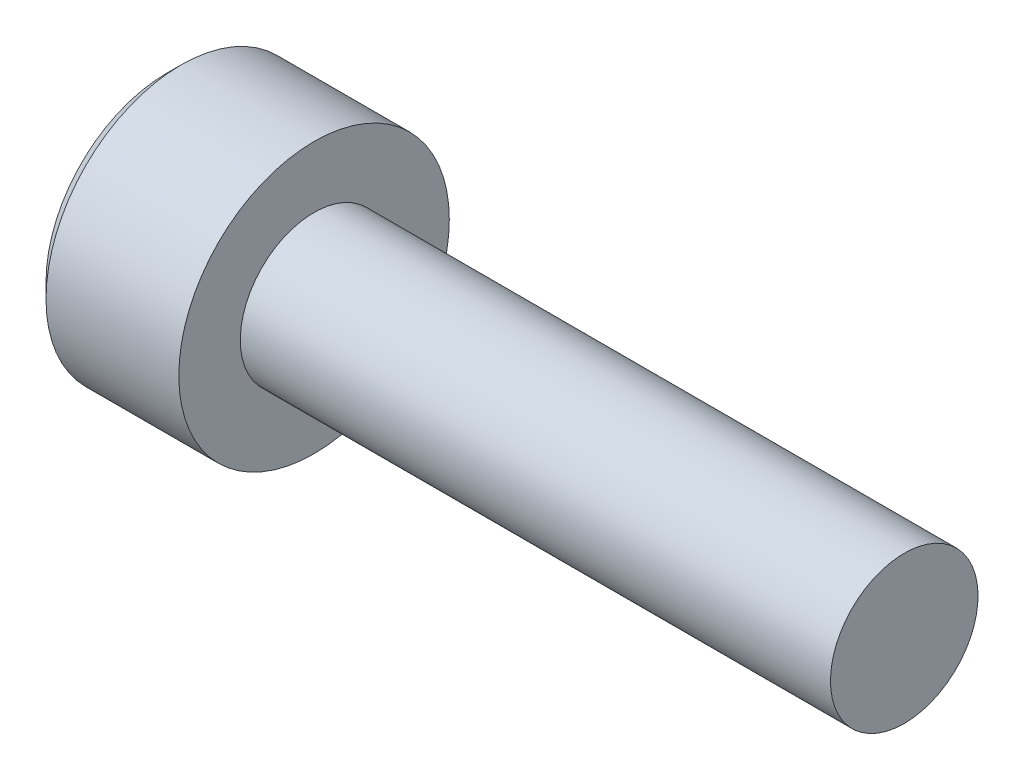
SolidWorks part; units mm, degrees
material "SUS304相当"
ref_plane "Front Plane" through (0, 0, 0) normal (0, 0, 1) x (1, 0, 0)
ref_plane "Top Plane" through (0, 0, 0) normal (0, 1, 0) x (1, 0, 0)
ref_plane "Right Plane" through (0, 0, 0) normal (1, 0, 0) x (0, 0, -1)
sketch "Sketch1" plane through (0, 0, 0) normal (0, 0, 1) x (1, 0, 0)
  line L0 (-3, 0) -> (12, 0) construction
  line L1 (0, 1.5) -> (12, 1.5)
  line L3 (-3, 0) -> (12, 0)
  line L4 (12, 1.5) -> (12, 0)
  line L6 (0, 1.5) -> (0, 2.75)
  line L7 (0, 2.75) -> (-3, 2.75)
  line L8 (-3, 0) -> (-3, 2.75)
  dimension "L" = 12
  dimension "M" = 3
  dimension "E" = 3
  dimension "A" = 5.5
revolve "Revolve1" add sketch "Sketch1" about L0
cosmetic thread "Thread1" parameters "L_s"=12, "ATD"=2.459
sketch "Sketch2" plane through (0, 0, 0) normal (0, 0, 1) x (1, 0, 0)
  line L0 (-3, 0) -> (-0.9489, 0) construction
  line L1 (-3, 0) -> (12, 0) construction
  line L2 (-0.9489, 0) -> (-1.7, 1.25)
  line L3 (-1.7, 1.25) -> (-3, 1.25)
  line L4 (-3, 0) -> (-3, 2.75) construction
  line L5 (-3, 1.25) -> (-3, 0)
  line L6 (-3, 0) -> (-0.9489, 0)
  dimension "MSM_1" = 1.3
  dimension "FIX_2" = 59
revolve "Cut-Revolve1" cut sketch "Sketch2" about L0
sketch "Sketch3" plane through (-3, 0, 0) normal (-1, 0, 0) x (0, 0, 1)
  line L0 (0, -3.025) -> (0, 3.025) construction
  line L1 (1.25, 0.7217) -> (0, 1.4434)
  line L2 (0, 1.4434) -> (-1.25, 0.7217)
  line L3 (-1.25, 0.7217) -> (-1.25, -0.7217)
  line L4 (-1.25, -0.7217) -> (0, -1.4434)
  line L5 (0, -1.4434) -> (1.25, -0.7217)
  line L6 (1.25, -0.7217) -> (1.25, 0.7217)
  circle A0 centre (0, 0) radius 1.25 construction
extrude "Cut-Extrude1" cut sketch "Sketch3" against normal blind 1.3
chamfer "Chamfer1" distance 0.3 1 edges at (-3, -2.75, 0)
